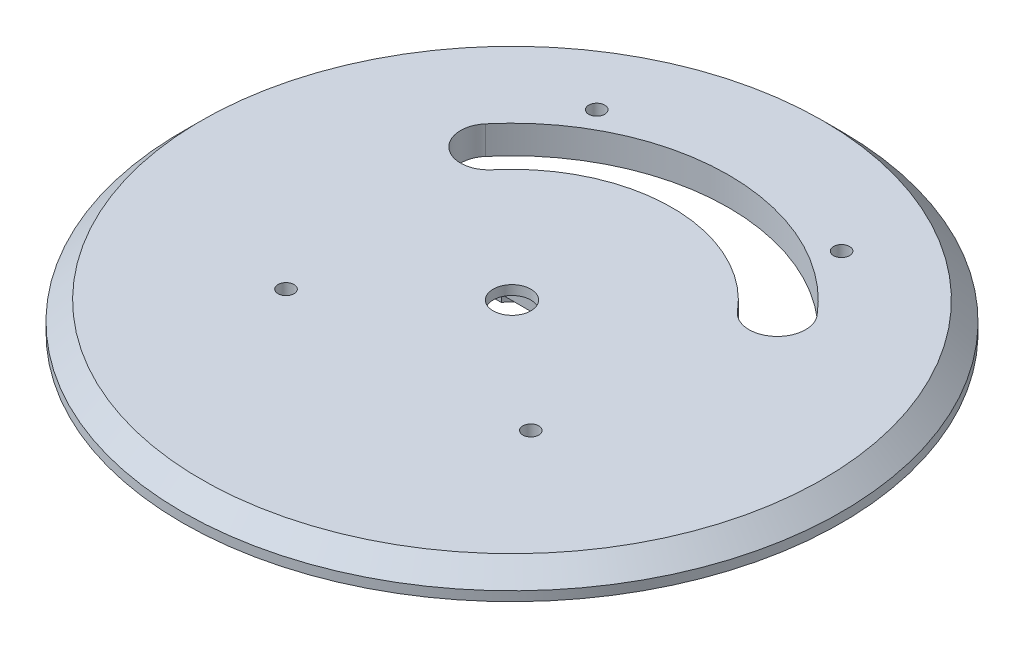
SolidWorks part; units mm, degrees
ref_plane "Front Plane" through (0, 0, 0) normal (0, 0, 1) x (1, 0, 0)
ref_plane "Top Plane" through (0, 0, 0) normal (0, 1, 0) x (1, 0, 0)
ref_plane "Right Plane" through (0, 0, 0) normal (1, 0, 0) x (0, 0, -1)
sketch "Sketch1" plane through (0, 0, 0) normal (0, 0, 1) x (1, 0, 0)
  line L0 (0, 40) -> (0, 70) construction
  line L1 (0, 53) -> (70, 53)
  line L2 (70, 53) -> (70, 55)
  line L3 (70, 55) -> (66, 59)
  line L4 (66, 59) -> (0, 59)
  line L5 (0, 59) -> (0, 53)
revolve "Turntable" add sketch "Sketch1" angle 360 about L0
sketch "Sketch2" plane through (0, 0, 0) normal (0, 1, 0) x (1, 0, 0)
  line L0 (-23.1, -4.4) -> (23.1, -4.4)
  line L1 (23.1, 4.4) -> (-23.1, 4.4)
  arc A0 (23.1, -4.4) -> (23.1, 4.4) centre (23.1, 0) ccw
  arc A1 (-23.1, 4.4) -> (-23.1, -4.4) centre (-23.1, 0) ccw
extrude "Horn dog pocket" cut sketch "Sketch2" along normal blind 4.2 from offset 52.8
sketch "Sketch3" plane through (0, 0, 0) normal (0, 1, 0) x (1, 0, 0)
  circle A0 centre (0, 0) radius 8
extrude "Hub relief" cut sketch "Sketch3" along normal blind 1.7 from offset 52.8
sketch "Sketch4" plane through (0, 0, 0) normal (0, 1, 0) x (1, 0, 0)
  circle A0 centre (0, 0) radius 4
  arc A1 (-35.238, 29.5682) -> (35.238, 29.5682) centre (0, 0) cw
  arc A2 (35.238, 29.5682) -> (26.0455, 21.8548) centre (30.6418, 25.7115) cw
  arc A3 (26.0455, 21.8548) -> (-26.0455, 21.8548) centre (0, 0) ccw
  arc A4 (-26.0455, 21.8548) -> (-35.238, 29.5682) centre (-30.6418, 25.7115) cw
extrude "Centre + cable kidney" cut sketch "Sketch4" along normal blind 6.4 from offset 52.8
sketch "Sketch5" plane through (0, 0, 0) normal (0, 1, 0) x (1, 0, 0)
  circle A0 centre (-26, 44) radius 1.7
  circle A1 centre (-26, -22) radius 1.7
  circle A2 centre (26, 44) radius 1.7
  circle A3 centre (26, -22) radius 1.7
extrude "Tower bolt holes" cut sketch "Sketch5" along normal blind 6.4 from offset 52.8
sketch "Sketch6" plane through (0, 0, 0) normal (0, 1, 0) x (1, 0, 0)
  line L0 (-23.05, 42.2968) -> (-26, 40.5936)
  line L1 (-26, 40.5936) -> (-28.95, 42.2968)
  line L2 (-28.95, 42.2968) -> (-28.95, 45.7032)
  line L3 (-28.95, 45.7032) -> (-26, 47.4064)
  line L4 (-26, 47.4064) -> (-23.05, 45.7032)
  line L5 (-23.05, 45.7032) -> (-23.05, 42.2968)
  line L6 (-23.05, -23.7032) -> (-26, -25.4064)
  line L7 (-26, -25.4064) -> (-28.95, -23.7032)
  line L8 (-28.95, -23.7032) -> (-28.95, -20.2968)
  line L9 (-28.95, -20.2968) -> (-26, -18.5936)
  line L10 (-26, -18.5936) -> (-23.05, -20.2968)
  line L11 (-23.05, -20.2968) -> (-23.05, -23.7032)
  line L12 (28.95, 42.2968) -> (26, 40.5936)
  line L13 (26, 40.5936) -> (23.05, 42.2968)
  line L14 (23.05, 42.2968) -> (23.05, 45.7032)
  line L15 (23.05, 45.7032) -> (26, 47.4064)
  line L16 (26, 47.4064) -> (28.95, 45.7032)
  line L17 (28.95, 45.7032) -> (28.95, 42.2968)
  line L18 (28.95, -23.7032) -> (26, -25.4064)
  line L19 (26, -25.4064) -> (23.05, -23.7032)
  line L20 (23.05, -23.7032) -> (23.05, -20.2968)
  line L21 (23.05, -20.2968) -> (26, -18.5936)
  line L22 (26, -18.5936) -> (28.95, -20.2968)
  line L23 (28.95, -20.2968) -> (28.95, -23.7032)
extrude "Tower nut pockets" cut sketch "Sketch6" along normal blind 2.9 from offset 52.8
